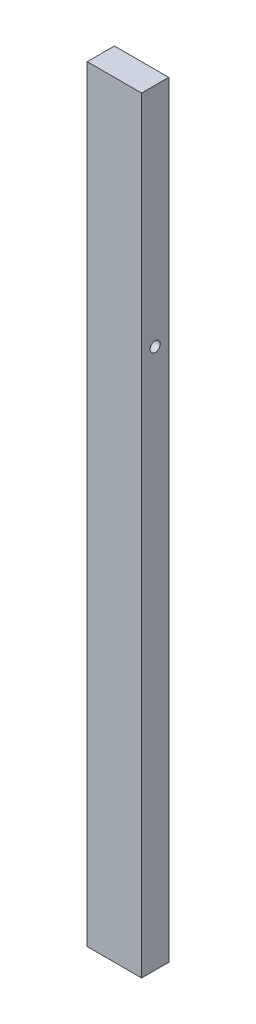
SolidWorks part; units mm, degrees
material "Sapin"
ref_plane "Plan de face" through (0, 0, 0) normal (0, 0, 1) x (1, 0, 0)
ref_plane "Plan de dessus" through (0, 0, 0) normal (0, 1, 0) x (1, 0, 0)
ref_plane "Plan de droite" through (0, 0, 0) normal (1, 0, 0) x (0, 0, -1)
sketch "Esquisse1" plane through (0, 0, 0) normal (0, 0, 1) x (1, 0, 0)
  line L1 (-24, -338.5) -> (24, -338.5)
  line L2 (-24, -338.5) -> (-24, 338.5)
  line L3 (-24, 338.5) -> (24, 338.5)
  line L4 (24, -338.5) -> (24, 338.5)
  line L5 (-24, -338.5) -> (24, 338.5) construction
  line L6 (-24, 338.5) -> (24, -338.5) construction
  point P0 (0, 0)
  dimension "D1" = 48
  dimension "D2" = 677
extrude "Boss.-Extru.1" add sketch "Esquisse1" along normal mid plane 24
sketch "Esquisse2" plane through (24, 0, 0) normal (1, 0, 0) x (0, 0, -1)
  line L0 (-12, -338.5) -> (12, -338.5) construction
  line L1 (-12, 338.5) -> (12, 338.5) construction
  circle A0 centre (0, 48.5) radius 1.75
  point P5 (0, -338.5)
  dimension "D1" = 3.5
  dimension "D2" = 290
extrude "Enlèv. mat.-Extru.1" [suppressed] cut sketch "Esquisse2" against normal through all
pattern_linear "Répétition linéaire1" [suppressed] count 7 spacing 15
sketch "Esquisse3" plane through (-24, 0, 0) normal (-1, 0, 0) x (0, 0, 1)
  line L0 (12, 338.5) -> (-12, 338.5) construction
  circle A0 centre (0, 138.5) radius 4.5
  dimension "D1" = 9
  dimension "D2" = 200
extrude "Enlèv. mat.-Extru.2" cut sketch "Esquisse3" against normal through all
sketch "Esquisse4" plane through (24, 0, 0) normal (1, 0, 0) x (0, 0, -1)
  circle A0 centre (0, 138.5) radius 6.75
  dimension "D1" = 13.5
extrude "Enlèv. mat.-Extru.3" [suppressed] cut sketch "Esquisse4" against normal blind 10
sketch "Esquisse5" plane through (-24, 0, 0) normal (-1, 0, 0) x (0, 0, 1)
  circle A0 centre (0, 138.5) radius 6.75
  dimension "D1" = 13.5
extrude "Enlèv. mat.-Extru.4" cut sketch "Esquisse5" against normal blind 10
